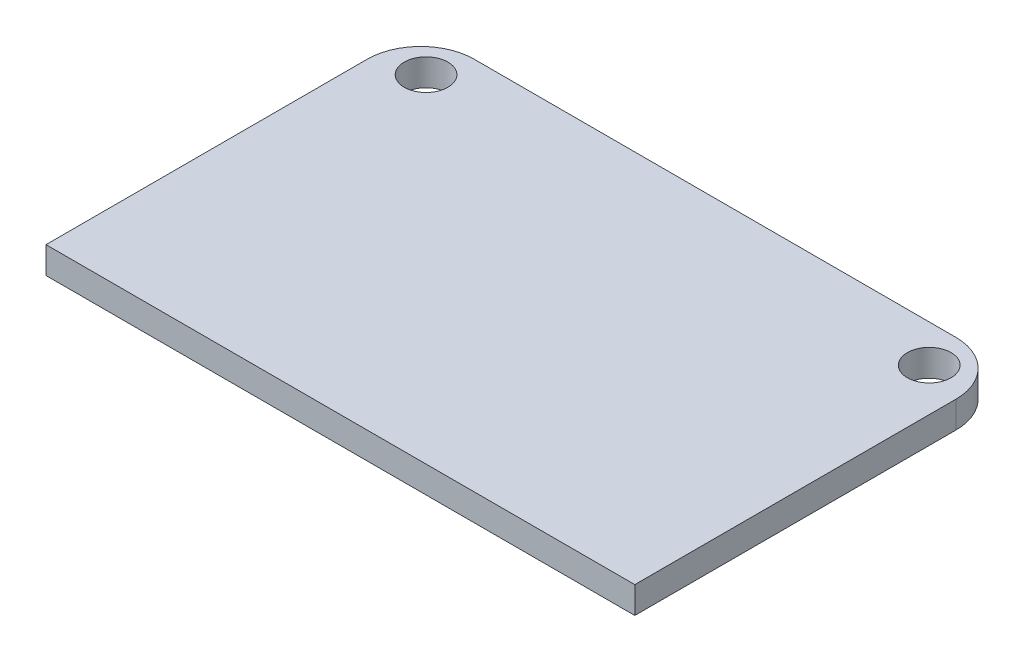
SolidWorks part; units mm, degrees
ref_plane "Front Plane" through (0, 0, 0) normal (0, 0, 1) x (1, 0, 0)
ref_plane "Top Plane" through (0, 0, 0) normal (0, 1, 0) x (1, 0, 0)
ref_plane "Right Plane" through (0, 0, 0) normal (1, 0, 0) x (0, 0, -1)
sketch "Sketch1" plane through (0, 0, 0) normal (0, 1, 0) x (1, 0, 0)
  line L0 (-12.2238, 0) -> (12.2238, 0) construction
  line L1 (-34.925, -22.225) -> (34.925, -22.225)
  line L2 (-34.925, -22.225) -> (-34.925, 22.225)
  line L3 (-34.925, 22.225) -> (34.925, 22.225)
  line L4 (34.925, -22.225) -> (34.925, 22.225)
  line L5 (-34.925, -22.225) -> (34.925, 22.225) construction
  line L6 (-34.925, 22.225) -> (34.925, -22.225) construction
  point P0 (0, 0)
  dimension "D1" = 69.85
  dimension "D2" = 44.45
extrude "Boss-Extrude1" add sketch "Sketch1" along normal blind 3.175
sketch "Sketch2" plane through (34.925, 0, 0) normal (1, 0, 0) x (0, 0, -1)
  line L0 (-22.225, 0) -> (-22.225, -19.05)
  line L1 (24.4475, 0) -> (-24.4475, 0) construction
  line L2 (-22.225, -19.05) -> (-18.161, -19.05)
  line L3 (-18.161, -19.05) -> (-18.161, -15.222)
  line L4 (-18.161, -15.222) -> (-15.0041, -12.065)
  line L5 (-15.0041, -12.065) -> (-12.682, -12.065)
  line L6 (-12.682, -12.065) -> (-9.525, -15.222)
  line L9 (-22.225, 0) -> (-9.525, 0)
  line L10 (-9.525, -15.222) -> (-9.525, 0)
  line L11 (-22.225, 3.175) -> (-22.225, 0) construction
  dimension "D1" = 12.065
  dimension "D2" = 19.05
  dimension "D3" = 2.3221
  dimension "D4" = 7.2209
  dimension "D5" = 12.7
  dimension "D6" = 4.064
extrude "Boss-Extrude2" [suppressed] add sketch "Sketch2" against normal blind 5.08 contours L6 L10 L9 L0 L2 L3 L4 L5
fillet "Fillet1" radius 6.35 2 edges at (-34.925, 1.5875, -22.225) (34.925, 1.5875, -22.225)
sketch "Sketch3" plane through (0, 0, 0) normal (0, -1, 0) x (1, 0, 0)
  point P0 (29.845, -17.78)
  point P1 (-29.845, -17.78)
hole_wizard "#6 (0.204) Diameter Hole1" positions "Sketch4" profile "Sketch6" hole size "#6" standard "ANSI Inch"
sketch "Sketch4" plane through (0, 0, 0) normal (0, -1, 0) x (-1, 0, 0)
  point P0 (-29.845, 17.78)
  point P3 (29.845, 17.78)
sketch "Sketch6" plane through (29.845, 0, -17.78) normal (1, 0, 0) x (0, 0, -1)
  line L0 (0, 0) -> (0, 39.6567)
  line L1 (0, 39.6567) -> (2.5908, 38.1)
  line L2 (2.5908, 38.1) -> (2.5908, 0)
  line L5 (2.5908, 0) -> (0, 0)
  line L10 (0, 39.6567) -> (-2.5908, 38.1) construction
  line L11 (0, -6.35) -> (0, 107.95) construction
  dimension "Hole Dia." = 5.1816
  dimension "Hole Depth" = 38.1
  dimension "Drill Angle" = 118
